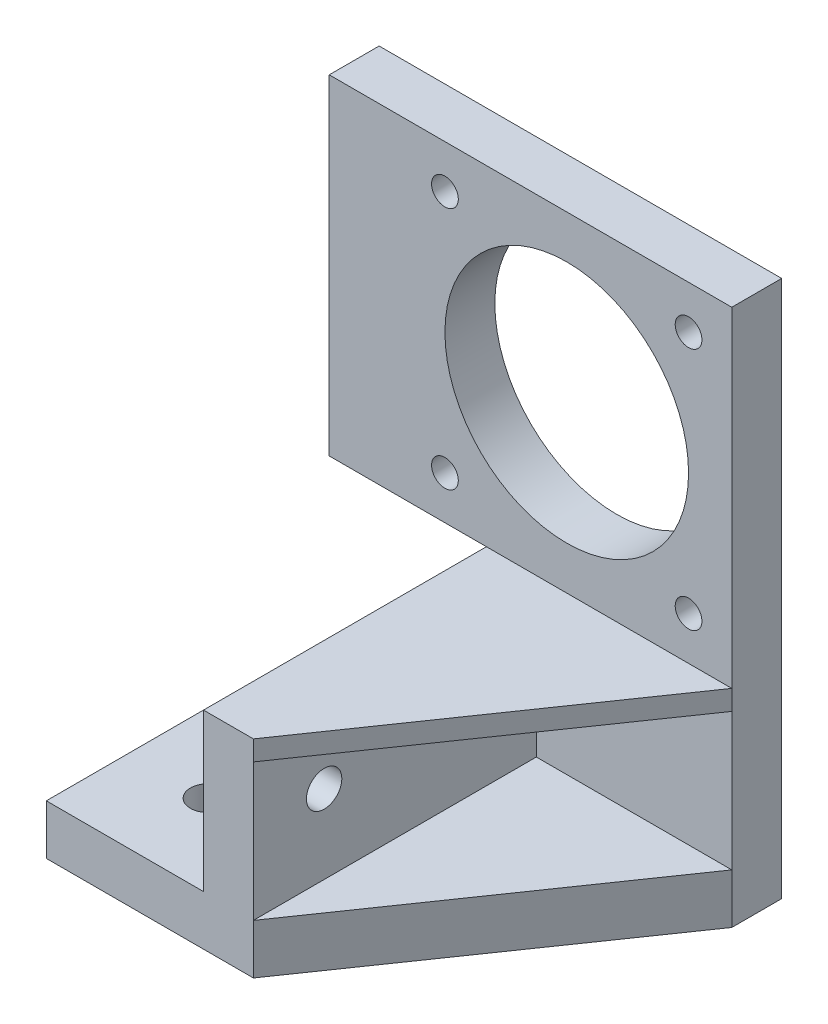
SolidWorks part; units mm, degrees
ref_plane "Front Plane" through (0, 0, 0) normal (0, 0, 1) x (1, 0, 0)
ref_plane "Top Plane" through (0, 0, 0) normal (0, 1, 0) x (1, 0, 0)
ref_plane "Right Plane" through (0, 0, 0) normal (1, 0, 0) x (0, 0, -1)
sketch "Sketch2" plane through (0, 0, 114.0386) normal (0, 0, 1) x (1, 0, 0)
  line L1 (10, -10) -> (-10, -10)
  line L2 (10, -10) -> (10, 10)
  line L3 (10, 10) -> (-10, 10)
  line L4 (-10, -10) -> (-10, 10)
  line L5 (10, -10) -> (-10, 10) construction
  line L6 (10, 10) -> (-10, -10) construction
  line L7 (-10, -10) -> (16.35, -10)
  line L8 (-10, -10) -> (-10, -16.35)
  line L9 (-10, -16.35) -> (16.35, -16.35)
  line L10 (16.35, -10) -> (16.35, -16.35)
  line L11 (16.35, -10) -> (10, -10)
  line L12 (16.35, -10) -> (16.35, 10)
  line L13 (16.35, 10) -> (10, 10)
  line L14 (10, -10) -> (10, 10)
  point P0 (0, 0)
  dimension "D1" = 6.35
  dimension "D2" = 6.35
  dimension "D3" = 20
extrude "Boss-Extrude1" add sketch "Sketch2" against normal blind 42.35 contours L10 L7 L1 L8 L9 | L12 L13 L2 L7
sketch "Sketch3" plane through (0, 0, 71.6886) normal (0, 0, -1) x (-1, 0, 0)
  line L0 (10, 3.138) -> (10, 8.5) construction
  line L1 (-16.35, 10) -> (0.7799, 10)
  line L2 (-16.35, 10) -> (-16.35, 16.35)
  line L3 (-16.35, 16.35) -> (0.7799, 16.35)
  line L4 (0.7799, 10) -> (0.7799, 16.35)
  line L5 (0.7799, 10) -> (-41.2201, 10)
  line L6 (0.7799, 10) -> (0.7799, 52)
  line L7 (0.7799, 52) -> (-41.2201, 52)
  line L8 (-41.2201, 10) -> (-41.2201, 52)
  line L15 (-35.7201, 15.5) -> (-4.7201, 46.5) construction
  line L16 (-35.7201, 46.5) -> (-4.7201, 15.5) construction
  line L17 (-41.2201, 10) -> (-16.35, 10)
  line L18 (-41.2201, 10) -> (-41.2201, -16.35)
  line L19 (-41.2201, -16.35) -> (-16.35, -16.35)
  line L20 (-16.35, 10) -> (-16.35, -16.35)
  line L23 (-35.7201, 15.5) -> (-4.7201, 46.5) construction
  line L24 (-35.7201, 46.5) -> (-4.7201, 15.5) construction
  line L25 (0.7799, 10) -> (10, 10)
  line L26 (0.7799, 10) -> (0.7799, 52)
  line L27 (0.7799, 52) -> (10, 52)
  line L28 (10, 10) -> (10, 52)
  circle A0 centre (-35.7201, 15.5) radius 1.7
  circle A1 centre (-35.7201, 46.5) radius 1.7
  circle A2 centre (-4.7201, 46.5) radius 1.7
  circle A3 centre (-4.7201, 15.5) radius 1.7
  circle A4 centre (-20.2201, 31) radius 15.5
  point P8 (-20.2201, 31)
  point P14 (-4.7201, 15.5)
  point P15 (-4.7201, 46.5)
  point P16 (-35.7201, 46.5)
  point P17 (-35.7201, 15.5)
  line M7 (-16.35, 10) -> (-16.35, -16.35)
  line M12 (-10, 10) -> (-16.35, 10)
  dimension "D5" = 3.4
  dimension "D6" = 5.5
  dimension "D1" = 6.35
  dimension "D2" = 42
  dimension "D3" = 42
  dimension "D4" = 31
  dimension "D7" = 0
extrude "Boss-Extrude2" add sketch "Sketch3" against normal blind 6.35 contours A4 L3 A3 L6 L7 L8 L5 L2 A2 A1 A0 | L18 L19 L5 M7 | A4 L3 L2 L1 L4 A3 M12 | L26 L25 L28 L27
sketch "Sketch4" plane through (0, -16.35, 0) normal (0, -1, 0) x (1, 0, 0)
  line L0 (16.35, 114.0386) -> (41.2201, 78.0386)
  line L1 (41.2201, 78.0386) -> (16.35, 78.0386)
  line L2 (16.35, 78.0386) -> (16.35, 114.0386)
extrude "Boss-Extrude4" add sketch "Sketch4" against normal blind 6.35
sketch "Sketch5" plane through (16.35, 0, 0) normal (1, 0, 0) x (0, 0, -1)
  line L0 (-96.0386, 10) -> (-96.0386, -10)
  line L1 (-78.0386, 10) -> (-114.0386, 10) construction
  line L2 (-114.0386, -10) -> (-78.0386, -10) construction
  line L3 (-96.0386, 0) -> (-114.0386, 0)
  line L4 (-114.0386, 10) -> (-114.0386, -10) construction
  line L5 (-96.0386, 0) -> (-78.0386, 0)
  line L6 (-78.0386, 10) -> (-78.0386, -10) construction
  point P13 (-87.0386, 0)
  point P14 (-105.0386, 0)
hole_wizard "M4 Clearance Hole1" positions "Sketch6" profile "Sketch7" hole size "M4" standard "ANSI Metric" end condition through all
sketch "Sketch6" plane through (16.35, 0, 0) normal (1, 0, 0) x (0, 0, -1)
  point P0 (-105.0386, 0)
  point P3 (-87.0386, 0)
sketch "Sketch7" plane through (16.35, 0, 105.0386) normal (0, 1, 0) x (0, 0, -1)
  line L0 (0, 0) -> (0, 26.35)
  line L1 (0, 26.35) -> (2.25, 26.35)
  line L2 (2.25, 26.35) -> (2.25, 0)
  line L5 (2.25, 0) -> (0, 0)
  line L11 (0, -6.35) -> (0, 107.95) construction
  dimension "Thru Hole Dia." = 4.5
  dimension "Thru Hole Depth" = 26.35
sketch "Sketch8" plane through (0, -16.35, 0) normal (0, -1, 0) x (1, 0, 0)
  line L0 (-10, 71.6886) -> (41.2201, 71.6886) construction
  line L1 (-10, 114.0386) -> (10, 114.0386)
  line L2 (-10, 114.0386) -> (-10, 71.6886)
  line L3 (-10, 71.6886) -> (10, 71.6886)
  line L4 (10, 114.0386) -> (10, 71.6886)
  line L5 (-10, 92.8636) -> (10, 92.8636)
  line L6 (0, 92.8636) -> (0, 71.6886)
  line L7 (0, 92.8636) -> (0, 114.0386)
  point P11 (0, 82.2761)
  point P13 (0, 103.4511)
  dimension "D1" = 20
hole_wizard "M4 Clearance Hole2" positions "Sketch9" profile "Sketch10" hole size "M4" standard "ANSI Metric" end condition through all
sketch "Sketch9" plane through (0, -16.35, 0) normal (0, -1, 0) x (-1, 0, 0)
  point P0 (0, -82.2761)
  point P3 (0, -103.4511)
sketch "Sketch10" plane through (0, -16.35, 82.2761) normal (1, 0, 0) x (0, 0, -1)
  line L0 (0, 0) -> (0, 68.35)
  line L1 (0, 68.35) -> (2.25, 68.35)
  line L2 (2.25, 68.35) -> (2.25, 0)
  line L5 (2.25, 0) -> (0, 0)
  line L11 (0, -6.35) -> (0, 107.95) construction
  dimension "Thru Hole Dia." = 4.5
  dimension "Thru Hole Depth" = 68.35
sketch "Sketch11" plane through (0, 10, 0) normal (0, 1, 0) x (1, 0, 0)
  line L0 (16.35, -114.0386) -> (41.2201, -78.0386)
  line L1 (41.2201, -78.0386) -> (16.35, -78.0386)
  line L2 (16.35, -78.0386) -> (16.35, -114.0386)
extrude "Boss-Extrude5" add sketch "Sketch11" against normal blind 2.54
